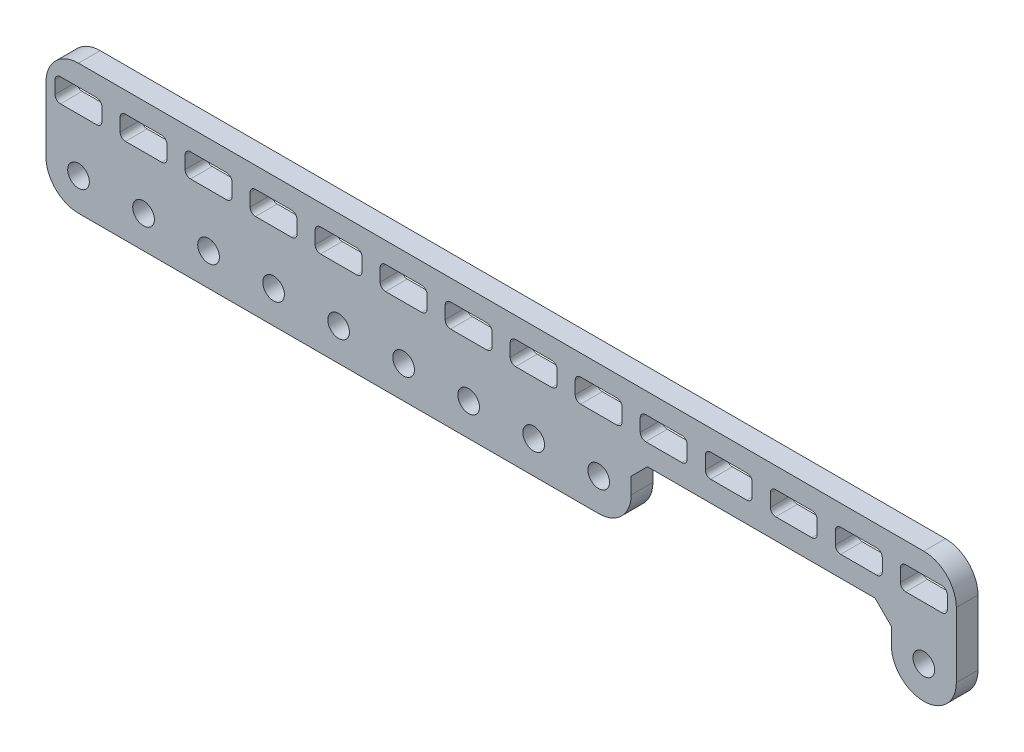
SolidWorks part; units mm, degrees
ref_plane "Alzado" through (0, 0, 0) normal (0, 0, 1) x (1, 0, 0)
ref_plane "Planta" through (0, 0, 0) normal (0, 1, 0) x (1, 0, 0)
ref_plane "Vista lateral" through (0, 0, 0) normal (1, 0, 0) x (0, 0, -1)
sketch "Model" plane through (0, 0, 0) normal (0, 0, 1) x (1, 0, 0)
  line L0 (238.4291, 228.7422) -> (355.4291, 228.7422)
  line L1 (310.4291, 210.7422) -> (238.4291, 210.7422)
  line L2 (359.9291, 224.2422) -> (359.9291, 215.2422)
  line L3 (233.9291, 224.2422) -> (233.9291, 215.2422)
  line L4 (249.9291, 222.6172) -> (244.9291, 222.6172)
  line L5 (244.1791, 223.3672) -> (244.1791, 225.1172)
  line L6 (244.9291, 225.8672) -> (249.9291, 225.8672)
  line L7 (250.6791, 225.1172) -> (250.6791, 223.3672)
  line L8 (285.9291, 222.6172) -> (280.9291, 222.6172)
  line L9 (280.1791, 223.3672) -> (280.1791, 225.1172)
  line L10 (280.9291, 225.8672) -> (285.9291, 225.8672)
  line L11 (286.6791, 225.1172) -> (286.6791, 223.3672)
  line L12 (240.9291, 222.6172) -> (235.9291, 222.6172)
  line L13 (235.1791, 223.3672) -> (235.1791, 225.1172)
  line L14 (235.9291, 225.8672) -> (240.9291, 225.8672)
  line L15 (241.6791, 225.1172) -> (241.6791, 223.3672)
  line L16 (276.9291, 222.6172) -> (271.9291, 222.6172)
  line L17 (271.1791, 223.3672) -> (271.1791, 225.1172)
  line L18 (271.9291, 225.8672) -> (276.9291, 225.8672)
  line L19 (277.6791, 225.1172) -> (277.6791, 223.3672)
  line L20 (294.9291, 222.6172) -> (289.9291, 222.6172)
  line L21 (289.1791, 223.3672) -> (289.1791, 225.1172)
  line L22 (289.9291, 225.8672) -> (294.9291, 225.8672)
  line L23 (295.6791, 225.1172) -> (295.6791, 223.3672)
  line L24 (303.9291, 222.6172) -> (298.9291, 222.6172)
  line L25 (298.1791, 223.3672) -> (298.1791, 225.1172)
  line L26 (298.9291, 225.8672) -> (303.9291, 225.8672)
  line L27 (304.6791, 225.1172) -> (304.6791, 223.3672)
  line L28 (321.9291, 222.6172) -> (316.9291, 222.6172)
  line L29 (316.1791, 223.3672) -> (316.1791, 225.1172)
  line L30 (316.9291, 225.8672) -> (321.9291, 225.8672)
  line L31 (322.6791, 225.1172) -> (322.6791, 223.3672)
  line L32 (312.9291, 222.6172) -> (307.9291, 222.6172)
  line L33 (307.1791, 223.3672) -> (307.1791, 225.1172)
  line L34 (307.9291, 225.8672) -> (312.9291, 225.8672)
  line L35 (313.6791, 225.1172) -> (313.6791, 223.3672)
  line L36 (357.9291, 222.6172) -> (352.9291, 222.6172)
  line L37 (352.1791, 223.3672) -> (352.1791, 225.1172)
  line L38 (352.9291, 225.8672) -> (357.9291, 225.8672)
  line L39 (358.6791, 225.1172) -> (358.6791, 223.3672)
  line L40 (348.9291, 222.6172) -> (343.9291, 222.6172)
  line L41 (343.1791, 223.3672) -> (343.1791, 225.1172)
  line L42 (343.9291, 225.8672) -> (348.9291, 225.8672)
  line L43 (349.6791, 225.1172) -> (349.6791, 223.3672)
  line L44 (339.9291, 222.6172) -> (334.9291, 222.6172)
  line L45 (334.1791, 223.3672) -> (334.1791, 225.1172)
  line L46 (334.9291, 225.8672) -> (339.9291, 225.8672)
  line L47 (340.6791, 225.1172) -> (340.6791, 223.3672)
  line L48 (330.9291, 222.6172) -> (325.9291, 222.6172)
  line L49 (325.1791, 223.3672) -> (325.1791, 225.1172)
  line L50 (325.9291, 225.8672) -> (330.9291, 225.8672)
  line L51 (331.6791, 225.1172) -> (331.6791, 223.3672)
  line L52 (317.1791, 219.7422) -> (348.6791, 219.7422)
  line L53 (314.9291, 215.2422) -> (314.9291, 217.4922)
  line L54 (350.9291, 215.2422) -> (350.9291, 217.4922)
  line L55 (350.9291, 217.4922) -> (348.6791, 219.7422)
  line L56 (314.9291, 217.4922) -> (317.1791, 219.7422)
  line L57 (267.9291, 222.6172) -> (262.9291, 222.6172)
  line L58 (262.1791, 223.3672) -> (262.1791, 225.1172)
  line L59 (262.9291, 225.8672) -> (267.9291, 225.8672)
  line L60 (268.6791, 225.1172) -> (268.6791, 223.3672)
  line L61 (258.9291, 222.6172) -> (253.9291, 222.6172)
  line L62 (253.1791, 223.3672) -> (253.1791, 225.1172)
  line L63 (253.9291, 225.8672) -> (258.9291, 225.8672)
  line L64 (259.6791, 225.1172) -> (259.6791, 223.3672)
  arc A0 (359.9291, 224.2422) -> (355.4291, 228.7422) centre (355.4291, 224.2422) ccw
  arc A1 (238.4291, 228.7422) -> (233.9291, 224.2422) centre (238.4291, 224.2422) ccw
  arc A2 (233.9291, 215.2422) -> (238.4291, 210.7422) centre (238.4291, 215.2422) ccw
  circle A3 centre (310.4291, 215.2422) radius 1.5
  circle A4 centre (292.4291, 215.2422) radius 1.5
  circle A5 centre (301.4291, 215.2422) radius 1.5
  circle A6 centre (274.4291, 215.2422) radius 1.5
  circle A7 centre (283.4291, 215.2422) radius 1.5
  circle A8 centre (247.4291, 215.2422) radius 1.5
  circle A9 centre (238.4291, 215.2422) radius 1.5
  circle A10 centre (355.4291, 215.2422) radius 1.5
  arc A11 (244.1791, 223.3672) -> (244.9291, 222.6172) centre (244.9291, 223.3672) ccw
  arc A12 (244.9291, 225.8672) -> (244.1791, 225.1172) centre (244.9291, 225.1172) ccw
  arc A13 (250.6791, 225.1172) -> (249.9291, 225.8672) centre (249.9291, 225.1172) ccw
  arc A14 (249.9291, 222.6172) -> (250.6791, 223.3672) centre (249.9291, 223.3672) ccw
  arc A15 (280.1791, 223.3672) -> (280.9291, 222.6172) centre (280.9291, 223.3672) ccw
  arc A16 (280.9291, 225.8672) -> (280.1791, 225.1172) centre (280.9291, 225.1172) ccw
  arc A17 (286.6791, 225.1172) -> (285.9291, 225.8672) centre (285.9291, 225.1172) ccw
  arc A18 (285.9291, 222.6172) -> (286.6791, 223.3672) centre (285.9291, 223.3672) ccw
  arc A19 (235.1791, 223.3672) -> (235.9291, 222.6172) centre (235.9291, 223.3672) ccw
  arc A20 (235.9291, 225.8672) -> (235.1791, 225.1172) centre (235.9291, 225.1172) ccw
  arc A21 (241.6791, 225.1172) -> (240.9291, 225.8672) centre (240.9291, 225.1172) ccw
  arc A22 (240.9291, 222.6172) -> (241.6791, 223.3672) centre (240.9291, 223.3672) ccw
  arc A23 (271.1791, 223.3672) -> (271.9291, 222.6172) centre (271.9291, 223.3672) ccw
  arc A24 (271.9291, 225.8672) -> (271.1791, 225.1172) centre (271.9291, 225.1172) ccw
  arc A25 (277.6791, 225.1172) -> (276.9291, 225.8672) centre (276.9291, 225.1172) ccw
  arc A26 (276.9291, 222.6172) -> (277.6791, 223.3672) centre (276.9291, 223.3672) ccw
  arc A27 (289.1791, 223.3672) -> (289.9291, 222.6172) centre (289.9291, 223.3672) ccw
  arc A28 (289.9291, 225.8672) -> (289.1791, 225.1172) centre (289.9291, 225.1172) ccw
  arc A29 (295.6791, 225.1172) -> (294.9291, 225.8672) centre (294.9291, 225.1172) ccw
  arc A30 (294.9291, 222.6172) -> (295.6791, 223.3672) centre (294.9291, 223.3672) ccw
  arc A31 (298.1791, 223.3672) -> (298.9291, 222.6172) centre (298.9291, 223.3672) ccw
  arc A32 (298.9291, 225.8672) -> (298.1791, 225.1172) centre (298.9291, 225.1172) ccw
  arc A33 (304.6791, 225.1172) -> (303.9291, 225.8672) centre (303.9291, 225.1172) ccw
  arc A34 (303.9291, 222.6172) -> (304.6791, 223.3672) centre (303.9291, 223.3672) ccw
  arc A35 (316.1791, 223.3672) -> (316.9291, 222.6172) centre (316.9291, 223.3672) ccw
  arc A36 (316.9291, 225.8672) -> (316.1791, 225.1172) centre (316.9291, 225.1172) ccw
  arc A37 (322.6791, 225.1172) -> (321.9291, 225.8672) centre (321.9291, 225.1172) ccw
  arc A38 (321.9291, 222.6172) -> (322.6791, 223.3672) centre (321.9291, 223.3672) ccw
  arc A39 (307.1791, 223.3672) -> (307.9291, 222.6172) centre (307.9291, 223.3672) ccw
  arc A40 (307.9291, 225.8672) -> (307.1791, 225.1172) centre (307.9291, 225.1172) ccw
  arc A41 (313.6791, 225.1172) -> (312.9291, 225.8672) centre (312.9291, 225.1172) ccw
  arc A42 (312.9291, 222.6172) -> (313.6791, 223.3672) centre (312.9291, 223.3672) ccw
  arc A43 (352.1791, 223.3672) -> (352.9291, 222.6172) centre (352.9291, 223.3672) ccw
  arc A44 (352.9291, 225.8672) -> (352.1791, 225.1172) centre (352.9291, 225.1172) ccw
  arc A45 (358.6791, 225.1172) -> (357.9291, 225.8672) centre (357.9291, 225.1172) ccw
  arc A46 (357.9291, 222.6172) -> (358.6791, 223.3672) centre (357.9291, 223.3672) ccw
  arc A47 (343.1791, 223.3672) -> (343.9291, 222.6172) centre (343.9291, 223.3672) ccw
  arc A48 (343.9291, 225.8672) -> (343.1791, 225.1172) centre (343.9291, 225.1172) ccw
  arc A49 (349.6791, 225.1172) -> (348.9291, 225.8672) centre (348.9291, 225.1172) ccw
  arc A50 (348.9291, 222.6172) -> (349.6791, 223.3672) centre (348.9291, 223.3672) ccw
  arc A51 (334.1791, 223.3672) -> (334.9291, 222.6172) centre (334.9291, 223.3672) ccw
  arc A52 (334.9291, 225.8672) -> (334.1791, 225.1172) centre (334.9291, 225.1172) ccw
  arc A53 (340.6791, 225.1172) -> (339.9291, 225.8672) centre (339.9291, 225.1172) ccw
  arc A54 (339.9291, 222.6172) -> (340.6791, 223.3672) centre (339.9291, 223.3672) ccw
  arc A55 (325.1791, 223.3672) -> (325.9291, 222.6172) centre (325.9291, 223.3672) ccw
  arc A56 (325.9291, 225.8672) -> (325.1791, 225.1172) centre (325.9291, 225.1172) ccw
  arc A57 (331.6791, 225.1172) -> (330.9291, 225.8672) centre (330.9291, 225.1172) ccw
  arc A58 (330.9291, 222.6172) -> (331.6791, 223.3672) centre (330.9291, 223.3672) ccw
  arc A59 (310.4291, 210.7422) -> (314.9291, 215.2422) centre (310.4291, 215.2422) ccw
  arc A60 (350.9291, 215.2422) -> (359.9291, 215.2422) centre (355.4291, 215.2422) ccw
  circle A61 centre (265.4291, 215.2422) radius 1.5
  circle A62 centre (256.4291, 215.2422) radius 1.5
  arc A63 (262.1791, 223.3672) -> (262.9291, 222.6172) centre (262.9291, 223.3672) ccw
  arc A64 (262.9291, 225.8672) -> (262.1791, 225.1172) centre (262.9291, 225.1172) ccw
  arc A65 (268.6791, 225.1172) -> (267.9291, 225.8672) centre (267.9291, 225.1172) ccw
  arc A66 (267.9291, 222.6172) -> (268.6791, 223.3672) centre (267.9291, 223.3672) ccw
  arc A67 (253.1791, 223.3672) -> (253.9291, 222.6172) centre (253.9291, 223.3672) ccw
  arc A68 (253.9291, 225.8672) -> (253.1791, 225.1172) centre (253.9291, 225.1172) ccw
  arc A69 (259.6791, 225.1172) -> (258.9291, 225.8672) centre (258.9291, 225.1172) ccw
  arc A70 (258.9291, 222.6172) -> (259.6791, 223.3672) centre (258.9291, 223.3672) ccw
extrude "Saliente-Extruir1" add sketch "Model" along normal blind 3
